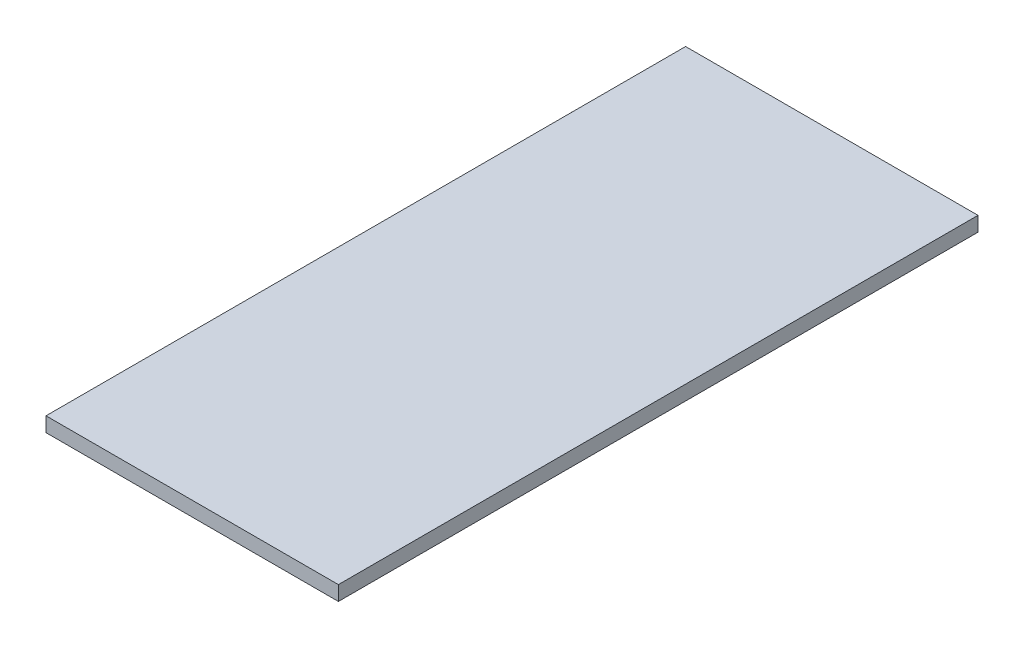
SolidWorks part; units mm, degrees
ref_plane "前视基准面" through (0, 0, 0) normal (0, 0, 1) x (1, 0, 0)
ref_plane "上视基准面" through (0, 0, 0) normal (0, 1, 0) x (1, 0, 0)
ref_plane "右视基准面" through (0, 0, 0) normal (1, 0, 0) x (0, 0, -1)
sketch "草图1" plane through (0, 0, 0) normal (0, 0, 1) x (1, 0, 0)
  line L1 (0, 0) -> (160, 0)
  line L2 (0, 0) -> (0, -8)
  line L3 (0, -8) -> (160, -8)
  line L4 (160, 0) -> (160, -8)
  dimension "D1" = 160
  dimension "D2" = 8
extrude "凸台-拉伸1" add sketch "草图1" along normal blind 350
